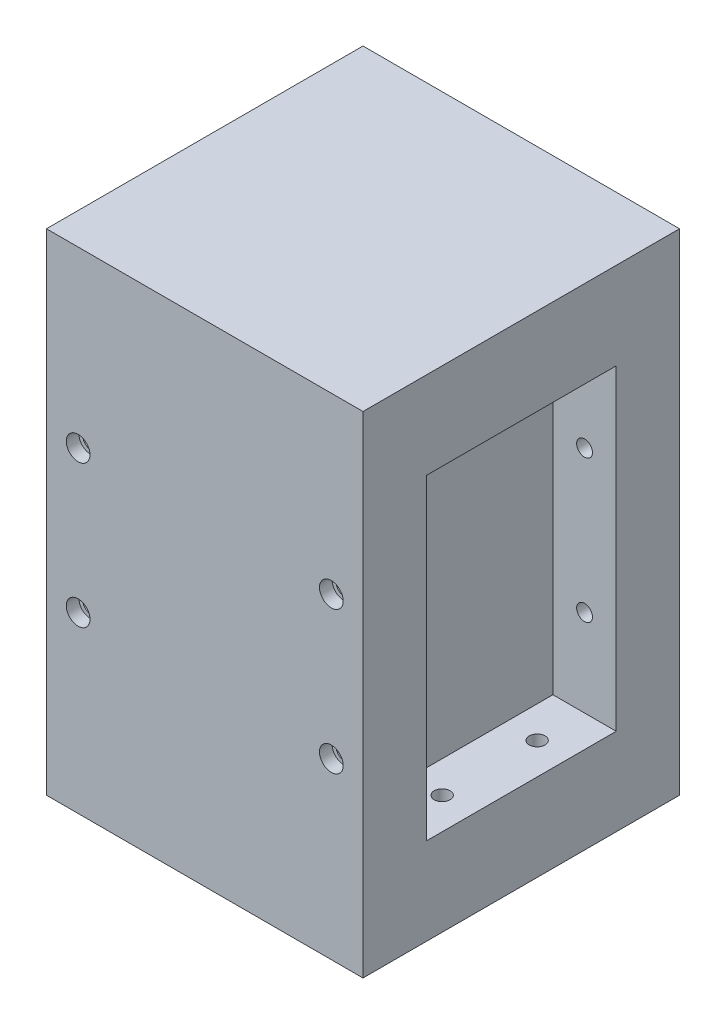
SolidWorks part; units mm, degrees
ref_plane "Front Plane" through (0, 0, 0) normal (0, 0, 1) x (1, 0, 0)
ref_plane "Top Plane" through (0, 0, 0) normal (0, 1, 0) x (1, 0, 0)
ref_plane "Right Plane" through (0, 0, 0) normal (1, 0, 0) x (0, 0, -1)
sketch "Sketch1" plane through (0, 0, 0) normal (0, 1, 0) x (1, 0, 0)
  line L0 (0, 0) -> (-62877.3227, 0) construction
  line L1 (0, 0) -> (0, -62877.3227) construction
  line L3 (-50, 50) -> (50, 50)
  line L4 (-50, 50) -> (-50, -50)
  line L5 (-50, -50) -> (50, -50)
  line L6 (50, 50) -> (50, -50)
  line L7 (-50, 50) -> (50, -50) construction
  line L8 (-50, -50) -> (50, 50) construction
  point P5 (0, 0)
  dimension "D1" = 100
extrude "Boss-Extrude1" add sketch "Sketch1" along normal blind 155 contours L4 L5 L6 L3
sketch "Sketch2" plane through (-50, 0, 0) normal (-1, 0, 0) x (0, 0, 1)
  line L0 (0, 0) -> (0, 50000) construction
  line L1 (-47.5, 77.5) -> (49952.5, 77.5) construction
  line L2 (-50, 155) -> (-50, 0) construction
  line L16 (-30, 127.5) -> (30, 127.5)
  line L21 (-30, 127.5) -> (-30, 27.5)
  line L22 (-30, 27.5) -> (30, 27.5)
  line L23 (30, 127.5) -> (30, 27.5)
  line L24 (-30, 127.5) -> (30, 27.5) construction
  line L25 (-30, 27.5) -> (30, 127.5) construction
  line L26 (-50, 155) -> (50, 155) construction
  point P7 (-50, 77.5)
  point P8 (0, 77.5)
  dimension "D1" = 77.5
  dimension "D3" = 60
  dimension "D2" = 100
extrude "Cut-Extrude1" cut sketch "Sketch2" against normal blind 20 contours L23 L22 L21 L16
mirror "Mirror1" about plane through (0, 0, 0) normal (1, 0, 0) of "Cut-Extrude1"
sketch "Sketch3" plane through (0, 0, 50) normal (0, 0, 1) x (1, 0, 0)
  line L0 (0, 0) -> (0, 50000) construction
  line L1 (-40, 145) -> (-40, -49855) construction
  line L3 (-50, 77.5) -> (49950, 77.5) construction
  line L4 (-50, 155) -> (-50, 0) construction
  circle A0 centre (-40, 100) radius 3.75
  circle A1 centre (-40, 55) radius 3.75
  circle A2 centre (40, 55) radius 3.75
  circle A3 centre (40, 100) radius 3.75
  point P9 (-50, 77.5)
  dimension "D2" = 7.5
  dimension "D3" = 22.5
  dimension "D1" = 10
extrude "Cut-Extrude2" cut sketch "Sketch3" against normal blind 4
mirror "Mirror2" about plane through (0, 0, 0) normal (0, 0, 1) of "Cut-Extrude2"
sketch "Sketch4" plane through (0, 0, 50) normal (0, 0, 1) x (1, 0, 0)
  line L0 (-50, 77.5) -> (49950, 77.5) construction
  line L1 (-50, 155) -> (-50, 0) construction
  line L2 (0, 0) -> (0, 50000) construction
  circle A0 centre (-40, 100) radius 2.5
  circle A1 centre (40, 100) radius 2.5
  circle A2 centre (40, 55) radius 2.5
  circle A3 centre (-40, 55) radius 2.5
  point P4 (-50, 77.5)
  dimension "D1" = 5
extrude "Cut-Extrude3" cut sketch "Sketch4" against normal through all
sketch "Sketch6" plane through (0, 0, 0) normal (0, -1, 0) x (1, 0, 0)
  line L0 (0, 0) -> (-50000, 0) construction
  line L1 (0, 0) -> (0, -50000) construction
  line L2 (-40, 43.43) -> (-40, -49956.57) construction
  line L4 (-50, -50) -> (-50, 50) construction
  circle A0 centre (-40, 15) radius 3.75
  circle A1 centre (40, 15) radius 3.75
  circle A2 centre (40, -15) radius 3.75
  circle A3 centre (-40, -15) radius 3.75
  dimension "D1" = 7.5
  dimension "D2" = 10
  dimension "D3" = 15
extrude "Cut-Extrude5" cut sketch "Sketch6" against normal blind 4
sketch "Sketch9" plane through (0, 0, 0) normal (0, -1, 0) x (1, 0, 0)
  line L0 (0, 0) -> (0, -50000) construction
  line L1 (0, 0) -> (-50000, 0) construction
  circle A0 centre (-40, 15) radius 2.5
  circle A1 centre (40, 15) radius 2.5
  circle A2 centre (40, -15) radius 2.5
  circle A3 centre (-40, -15) radius 2.5
  dimension "D1" = 5
extrude "Cut-Extrude7" cut sketch "Sketch9" against normal blind 50
